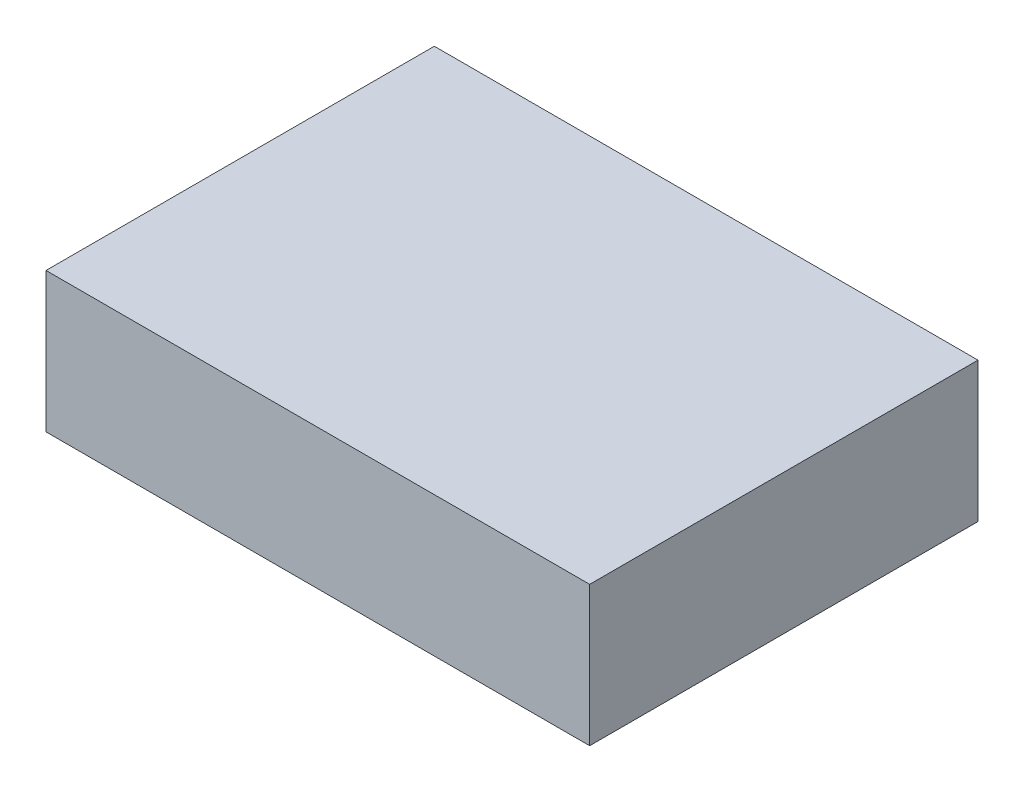
SolidWorks part; units mm, degrees
ref_plane "前视基准面" through (0, 0, 0) normal (0, 0, 1) x (1, 0, 0)
ref_plane "上视基准面" through (0, 0, 0) normal (0, 1, 0) x (1, 0, 0)
ref_plane "右视基准面" through (0, 0, 0) normal (1, 0, 0) x (0, 0, -1)
sketch "草图1" plane through (0, 0, 0) normal (0, 1, 0) x (1, 0, 0)
  line L1 (35, -25) -> (-35, -25)
  line L2 (35, -25) -> (35, 25)
  line L3 (35, 25) -> (-35, 25)
  line L4 (-35, -25) -> (-35, 25)
  line L5 (0, 25) -> (0, -25) construction
  line L6 (35, 0) -> (-35, 0) construction
  point P0 (0, 0)
extrude "凸台-拉伸1" add sketch "草图1" along normal blind 18
